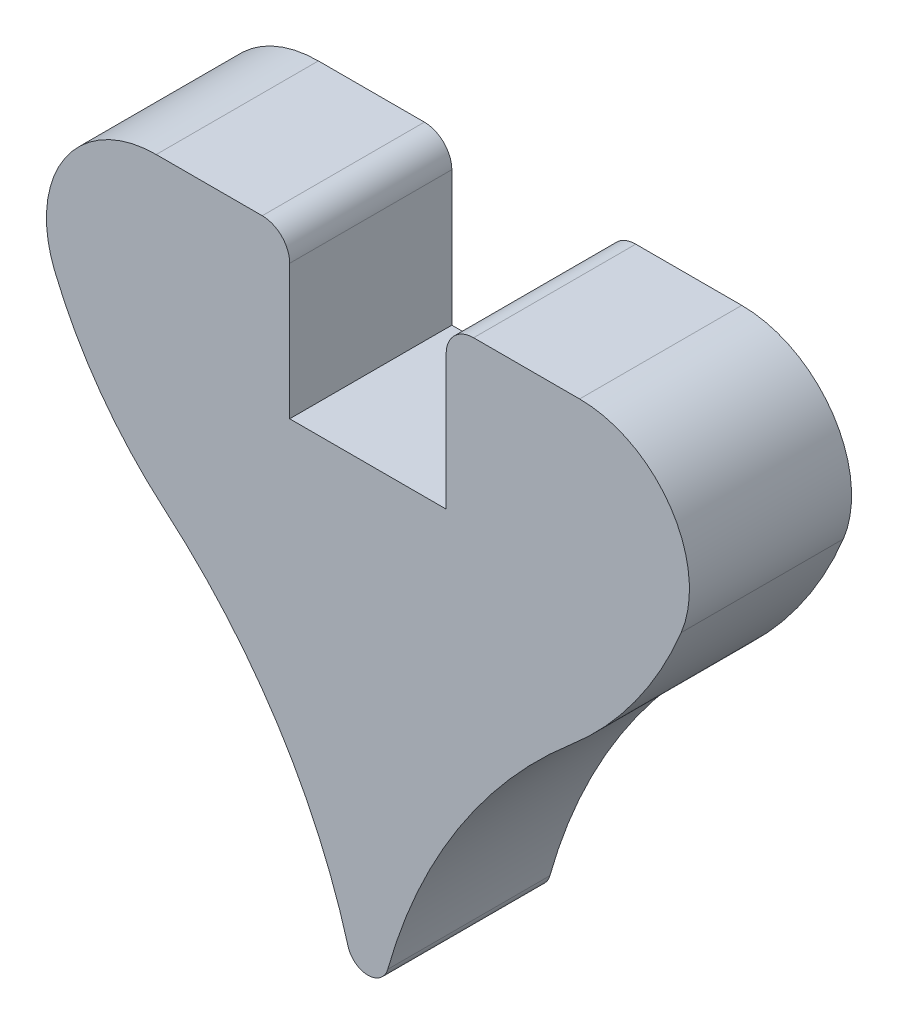
SolidWorks part; units mm, degrees
material "Acrylic (Medium-high impact)"
ref_plane "Front Plane" through (0, 0, 0) normal (0, 0, 1) x (1, 0, 0)
ref_plane "Top Plane" through (0, 0, 0) normal (0, 1, 0) x (1, 0, 0)
ref_plane "Right Plane" through (0, 0, 0) normal (1, 0, 0) x (0, 0, -1)
sketch "스케치1" plane through (0, 0, 0) normal (0, 0, 1) x (1, 0, 0)
  line L0 (0, 2.0297) -> (0, 0) construction
  line L1 (-6.35, -3.5297) -> (6.35, -3.5297) construction
  line L2 (-6.35, -3.5297) -> (-6.35, 3.5297) construction
  line L3 (-6.35, 3.5297) -> (6.35, 3.5297) construction
  line L4 (6.35, -3.5297) -> (6.35, 3.5297) construction
  line L5 (-6.35, -3.5297) -> (6.35, 3.5297) construction
  line L6 (-6.35, 3.5297) -> (6.35, -3.5297) construction
  line L7 (-1.4475, 0.5297) -> (1.4475, 0.5297)
  line L8 (-1.4475, 0.5297) -> (-1.4475, 3.5297)
  line L9 (-1.4475, 3.5297) -> (1.4475, 3.5297) construction
  line L10 (1.4475, 0.5297) -> (1.4475, 3.5297)
  line L11 (-1.4475, 0.5297) -> (1.4475, 3.5297) construction
  line L12 (-1.4475, 3.5297) -> (1.4475, 0.5297) construction
  line L13 (0, 2.0297) -> (0, -8.3842) construction
  line L14 (-6.35, 3.5297) -> (-1.4475, 3.5297)
  line L15 (1.4475, 3.5297) -> (6.35, 3.5297)
  line L16 (-1.4475, 3.5297) -> (-6.35, 3.5297)
  arc A0 (-6.35, 3.5297) -> (-3.7563, -2.088) centre (1.0306, 3.5297) ccw
  arc A1 (-3.7563, -2.088) -> (0, -9.4434) centre (-10.7515, -10.2972) cw
  arc A2 (3.7563, -2.088) -> (0, -9.4434) centre (10.7515, -10.2972) ccw
  arc A3 (6.35, 3.5297) -> (3.7563, -2.088) centre (-1.0306, 3.5297) cw
  point P0 (0, 0)
  point P5 (0, 2.0297)
  dimension "D1" = 3
  dimension "D2" = 2.895
  dimension "D3" = 12.7
extrude "보스-돌출1" add sketch "스케치1" along normal blind 3 contours A3 L15 L10 L7 L8 L14 A0 A1 A2
fillet "필렛1" radius 0.381 1 edges at (0, -9.4434, 1.5)
fillet "필렛2" radius 2.032 2 edges at (-6.35, 3.5297, 1.5) (6.35, 3.5297, 1.5)
fillet "필렛3" radius 0.508 2 edges at (1.4475, 3.5297, 1.5) (-1.4475, 3.5297, 1.5)
